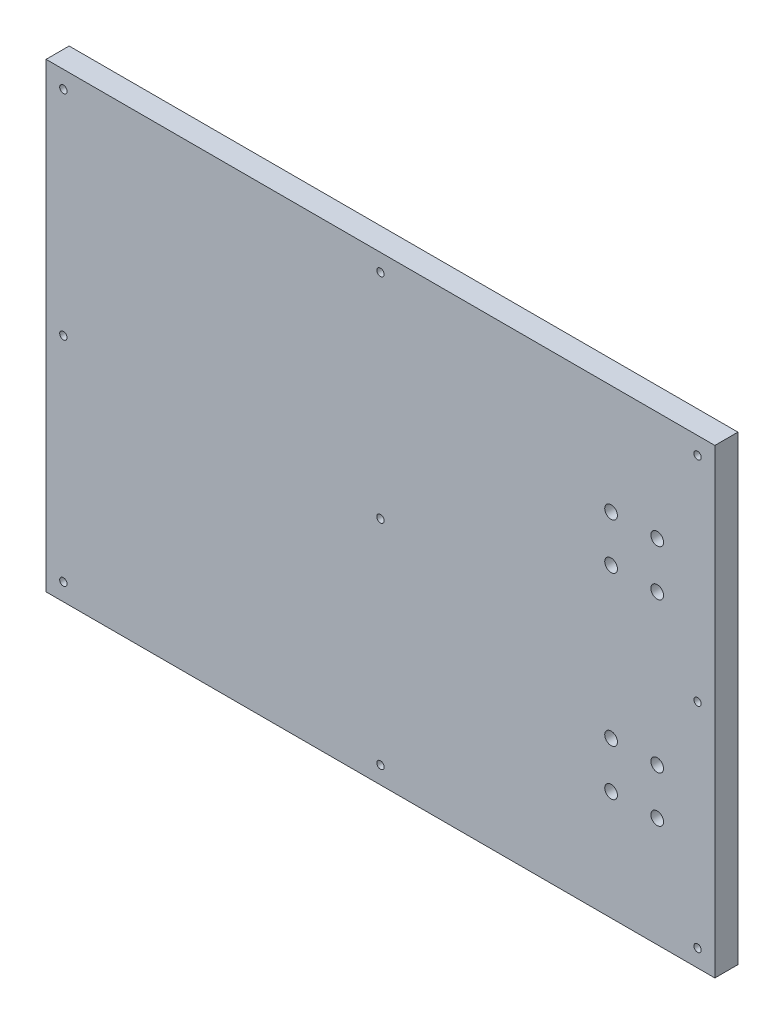
SolidWorks part; units mm, degrees
ref_plane "前视基准面" through (0, 0, 0) normal (0, 0, 1) x (1, 0, 0)
ref_plane "上视基准面" through (0, 0, 0) normal (0, 1, 0) x (1, 0, 0)
ref_plane "右视基准面" through (0, 0, 0) normal (1, 0, 0) x (0, 0, -1)
sketch "Model" plane through (0, 0, 0) normal (0, 0, 1) x (1, 0, 0)
  line L0 (787.697, 372.4613) -> (497.697, 372.4613)
  line L1 (497.697, 172.4613) -> (787.697, 172.4613)
  line L2 (787.697, 172.4613) -> (787.697, 372.4613)
  line L3 (497.697, 172.4613) -> (497.697, 372.4613)
  circle A0 centre (742.697, 219.9613) radius 2.75
  circle A1 centre (762.697, 219.9613) radius 2.75
  circle A2 centre (742.697, 239.9613) radius 2.75
  circle A3 centre (762.697, 239.9613) radius 2.75
  circle A4 centre (742.697, 324.9613) radius 2.75
  circle A5 centre (762.697, 324.9613) radius 2.75
  circle A6 centre (742.697, 304.9613) radius 2.75
  circle A7 centre (762.697, 304.9613) radius 2.75
  circle A8 centre (642.697, 364.9613) radius 1.6
  circle A9 centre (642.697, 179.9613) radius 1.6
  circle A10 centre (505.197, 272.4613) radius 1.6
  circle A11 centre (780.197, 272.4613) radius 1.6
  circle A12 centre (642.697, 272.4613) radius 1.6
  circle A13 centre (780.197, 364.9613) radius 1.6
  circle A14 centre (505.197, 364.9613) radius 1.6
  circle A15 centre (780.197, 179.9613) radius 1.6
  circle A16 centre (505.197, 179.9613) radius 1.6
extrude "凸台-拉伸1" add sketch "Model" along normal blind 10
